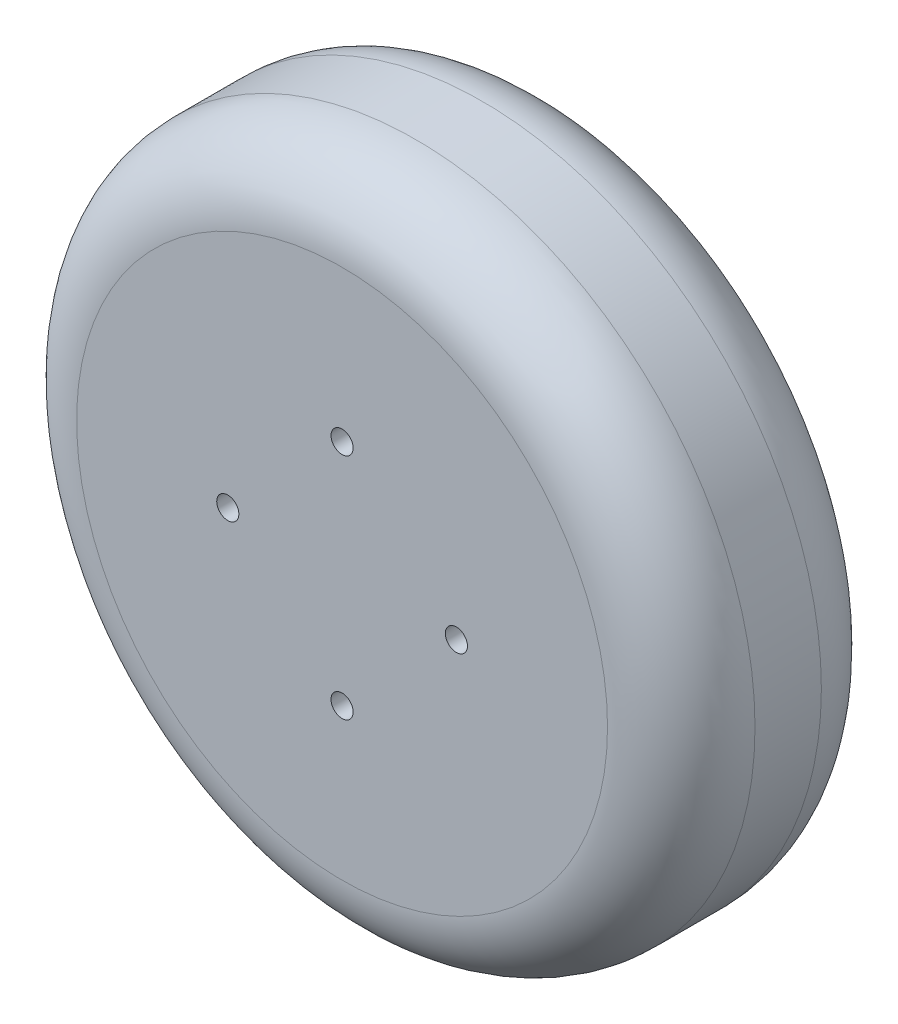
SolidWorks part; units mm, degrees
ref_plane "前视基准面" through (0, 0, 0) normal (0, 0, 1) x (1, 0, 0)
ref_plane "上视基准面" through (0, 0, 0) normal (0, 1, 0) x (1, 0, 0)
ref_plane "右视基准面" through (0, 0, 0) normal (1, 0, 0) x (0, 0, -1)
sketch "草图1" plane through (0, 0, 0) normal (0, 0, 1) x (1, 0, 0)
  circle A0 centre (0, 0) radius 15.5 construction
  circle A1 centre (0, -15.5) radius 1.5
  circle A2 centre (-15.5, 0) radius 1.5
  circle A3 centre (0, 15.5) radius 1.5
  circle A4 centre (15.5, 0) radius 1.5
  circle A5 centre (0, 0) radius 46
  dimension "D1" = 31
  dimension "D2" = 3
  dimension "D4" = 92
  dimension "D3" = 4
extrude "凸台-拉伸1" add sketch "草图1" along normal blind 29 contours A5
fillet "圆角1" radius 10 1 edges at (46, 0, 29)
fillet "圆角2" radius 10 1 edges at (46, 0, 0)
